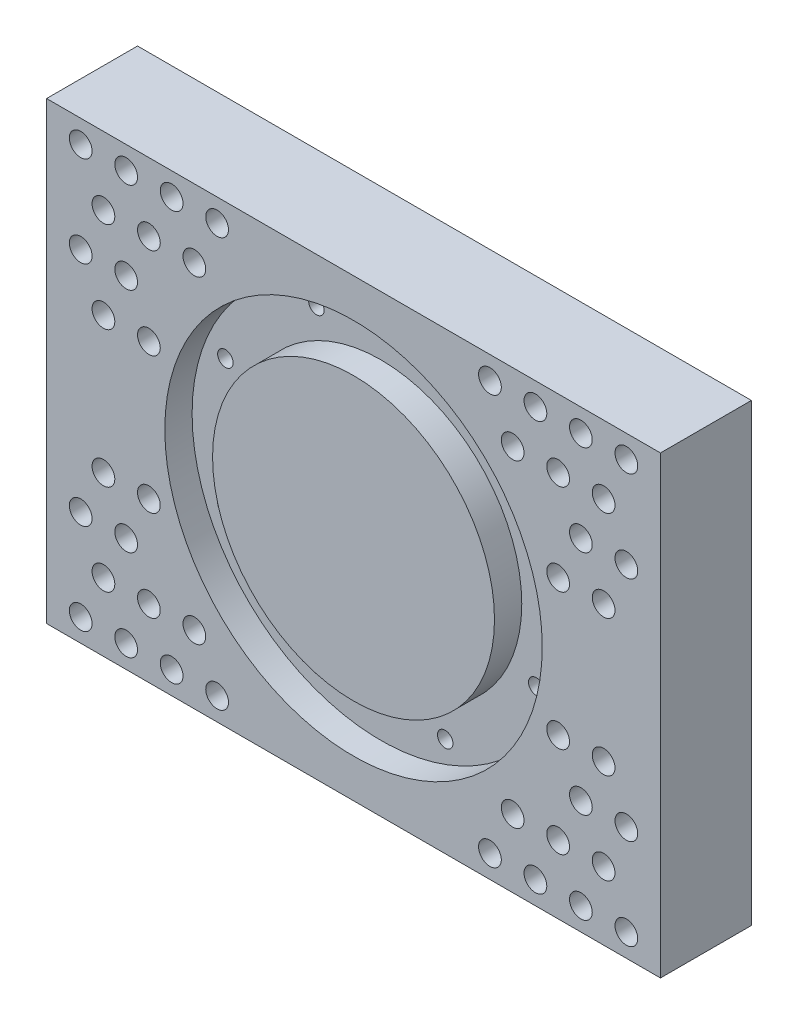
SolidWorks part; units mm, degrees
ref_plane "前视基准面" through (0, 0, 0) normal (0, 0, 1) x (1, 0, 0)
ref_plane "上视基准面" through (0, 0, 0) normal (0, 1, 0) x (1, 0, 0)
ref_plane "右视基准面" through (0, 0, 0) normal (1, 0, 0) x (0, 0, -1)
other "Configuration Table"
sketch "草图1" plane through (0, 0, 0) normal (0, 0, 1) x (1, 0, 0)
  line L1 (-67.5, -50) -> (67.5, -50)
  line L2 (-67.5, -50) -> (-67.5, 50)
  line L3 (-67.5, 50) -> (67.5, 50)
  line L4 (67.5, -50) -> (67.5, 50)
  line L5 (-67.5, -50) -> (67.5, 50) construction
  line L6 (-67.5, 50) -> (67.5, -50) construction
  point P0 (0, 0)
  dimension "D1" = 100
  dimension "D2" = 135
extrude "凸台-拉伸1" add sketch "草图1" along normal blind 20
sketch "草图2" plane through (0, 0, 20) normal (0, 0, 1) x (1, 0, 0)
  line L0 (0, -50) -> (0, 50) construction
  line L1 (-67.5, -50) -> (67.5, -50) construction
  line L2 (67.5, 50) -> (-67.5, 50) construction
  line L3 (14.1593, 34.1835) -> (0, 0)
  circle A0 centre (0, 0) radius 40
  circle A1 centre (0, 0) radius 37
  circle A2 centre (14.1593, 34.1835) radius 1.7
  circle A3 centre (34.1835, 14.1593) radius 1.7
  circle A4 centre (34.1835, -14.1593) radius 1.7
  circle A5 centre (14.1593, -34.1835) radius 1.7
  circle A6 centre (-14.1593, -34.1835) radius 1.7
  circle A7 centre (-34.1835, -14.1593) radius 1.7
  circle A8 centre (-34.1835, 14.1593) radius 1.7
  circle A9 centre (-14.1593, 34.1835) radius 1.7
  point P29 (0, 0)
  dimension "D1" = 80
  dimension "D2" = 74
  dimension "D3" = 3.4
  dimension "D4" = 22.5
  dimension "D5" = 8
extrude "切除-拉伸1" cut sketch "草图2" against normal blind 20 contours A3 | A2 | A9 | A8 | A7 | A6 | A5 | A4
sketch "草图3" plane through (0, 0, 20) normal (0, 0, 1) x (1, 0, 0)
  circle A0 centre (0, 0) radius 41.5
  circle A1 centre (0, 0) radius 31
  dimension "D1" = 83
  dimension "D2" = 62
extrude "切除-拉伸2" cut sketch "草图3" against normal blind 6
sketch "草图4" plane through (0, 0, 20) normal (0, 0, 1) x (1, 0, 0)
  line L0 (-67.5, 50) -> (-67.5, -50) construction
  line L1 (67.5, 50) -> (-67.5, 50) construction
  line L2 (0, 0) -> (0, 50) construction
  line L3 (0, 0) -> (-67.5, 0) construction
  circle A0 centre (-60, 45) radius 2.5
  circle A1 centre (-50, 45) radius 2.5
  circle A2 centre (-55, 35) radius 2.5
  circle A3 centre (-40, 45) radius 2.5
  circle A4 centre (-45, 35) radius 2.5
  circle A5 centre (-30, 45) radius 2.5
  circle A6 centre (-35, 35) radius 2.5
  circle A7 centre (-50, 25) radius 2.5
  circle A8 centre (-55, 15) radius 2.5
  circle A9 centre (-60, 25) radius 2.5
  circle A10 centre (-45, 15) radius 2.5
  circle A11 centre (45, 15) radius 2.5
  circle A12 centre (60, 25) radius 2.5
  circle A13 centre (55, 15) radius 2.5
  circle A14 centre (50, 25) radius 2.5
  circle A15 centre (35, 35) radius 2.5
  circle A16 centre (30, 45) radius 2.5
  circle A17 centre (45, 35) radius 2.5
  circle A18 centre (40, 45) radius 2.5
  circle A19 centre (55, 35) radius 2.5
  circle A20 centre (50, 45) radius 2.5
  circle A21 centre (60, 45) radius 2.5
  circle A22 centre (60, -45) radius 2.5
  circle A23 centre (50, -45) radius 2.5
  circle A24 centre (55, -35) radius 2.5
  circle A25 centre (40, -45) radius 2.5
  circle A26 centre (45, -35) radius 2.5
  circle A27 centre (30, -45) radius 2.5
  circle A28 centre (35, -35) radius 2.5
  circle A29 centre (50, -25) radius 2.5
  circle A30 centre (55, -15) radius 2.5
  circle A31 centre (60, -25) radius 2.5
  circle A32 centre (45, -15) radius 2.5
  circle A33 centre (-45, -15) radius 2.5
  circle A34 centre (-60, -25) radius 2.5
  circle A35 centre (-55, -15) radius 2.5
  circle A36 centre (-50, -25) radius 2.5
  circle A37 centre (-35, -35) radius 2.5
  circle A38 centre (-30, -45) radius 2.5
  circle A39 centre (-45, -35) radius 2.5
  circle A40 centre (-40, -45) radius 2.5
  circle A41 centre (-55, -35) radius 2.5
  circle A42 centre (-50, -45) radius 2.5
  circle A43 centre (-60, -45) radius 2.5
  dimension "D1" = 5
  dimension "D2" = 5
  dimension "D3" = 5
  dimension "D7" = 7.5
  dimension "D8" = 5
  dimension "D9" = 5
  dimension "D4" = 10
  dimension "D5" = 10
  dimension "D6" = 5
  dimension "D12" = 60
  dimension "D13" = 50
  dimension "D10" = 3
  dimension "D11" = 2
extrude "切除-拉伸3" cut sketch "草图4" against normal up to next (20 mm away)
